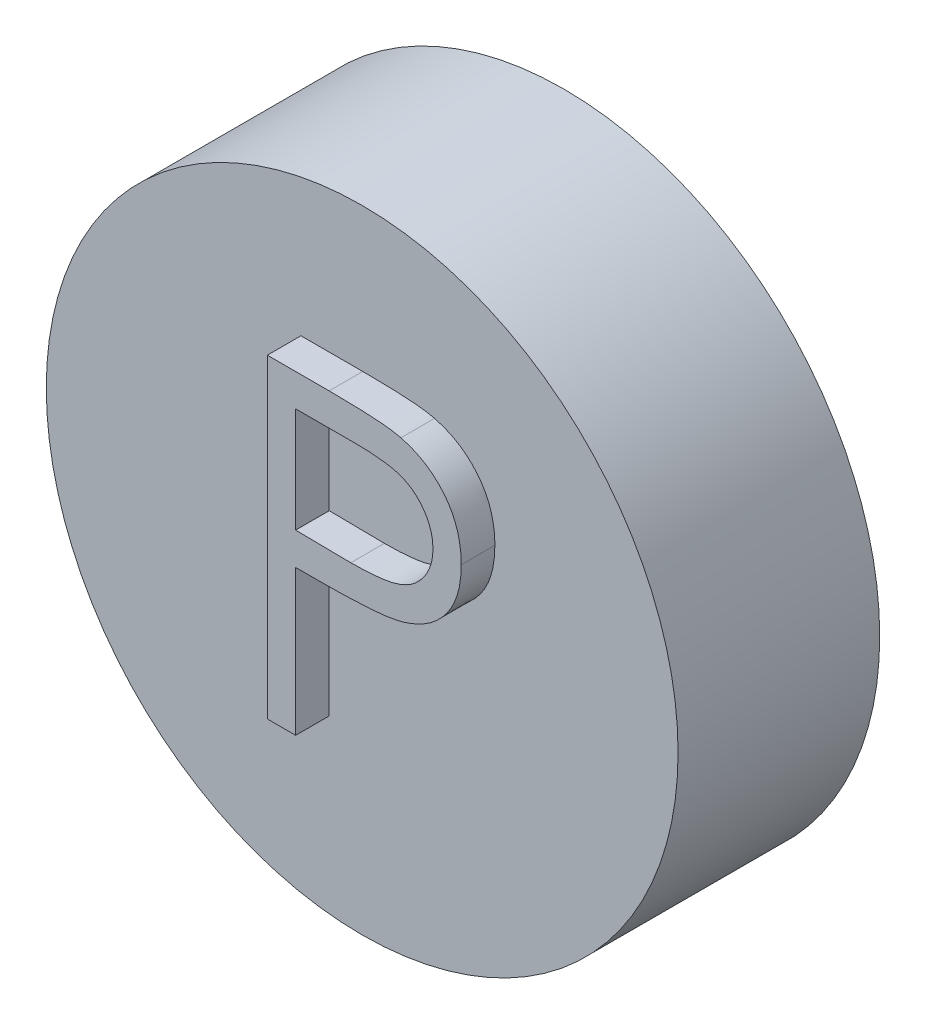
SolidWorks part; units mm, degrees
ref_plane "Front Plane" through (0, 0, 0) normal (0, 0, 1) x (1, 0, 0)
ref_plane "Top Plane" through (0, 0, 0) normal (0, 1, 0) x (1, 0, 0)
ref_plane "Right Plane" through (0, 0, 0) normal (1, 0, 0) x (0, 0, -1)
sketch "Sketch1" plane through (0, 0, 0) normal (0, 0, 1) x (1, 0, 0)
  circle A0 centre (0, 0) radius 8.763
  circle A1 centre (0, 0) radius 11.938
  dimension "D1" = 17.526
  dimension "D2" = 23.876
extrude "Boss-Extrude1" add sketch "Sketch1" along normal blind 5.08
sketch "Sketch2" plane through (0, 0, 5.08) normal (0, 0, 1) x (1, 0, 0)
  circle A0 centre (0, 0) radius 11.938
extrude "Boss-Extrude2" add sketch "Sketch2" along normal blind 2.54
sketch "Sketch3" plane through (0, 0, 7.62) normal (0, 0, 1) x (1, 0, 0)
  text T0 "P" font "Century Gothic" height in points 45
  point P1 (0, 0)
  point P3 (0, 0)
  point P4 (0, 0)
  point P5 (-1.6742, -2.3551)
  point P6 (0, 0)
  point P7 (-2.1207, -2.8015)
  point P8 (-3.8396, -5.391)
extrude "Boss-Extrude3" add sketch "Sketch3" along normal blind 1.27
